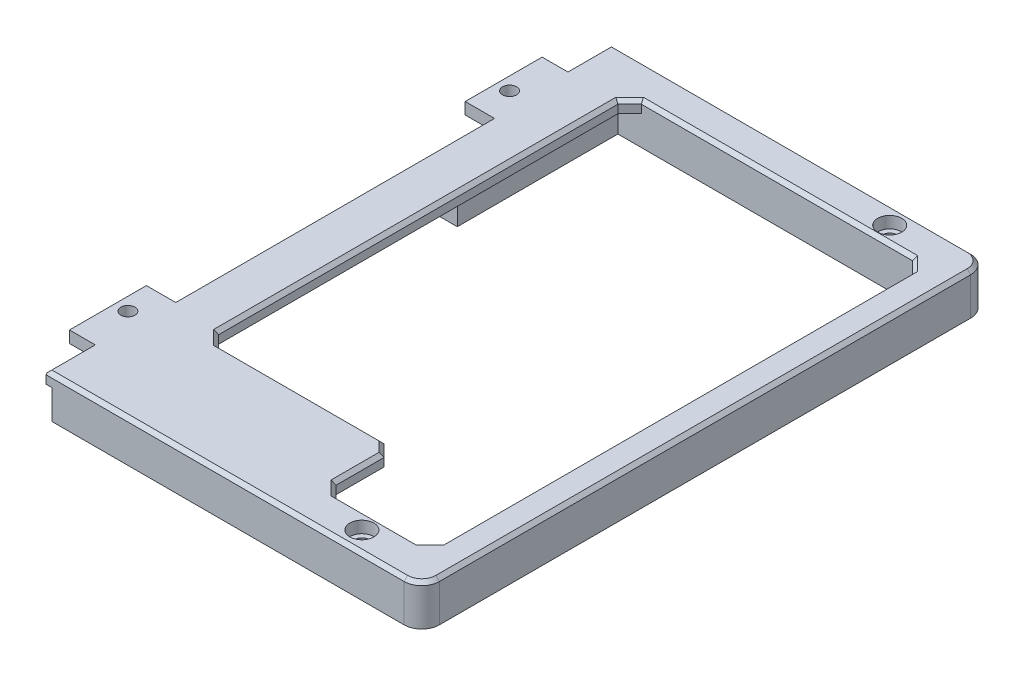
SolidWorks part; units mm, degrees
ref_plane "前视基准面" through (0, 0, 0) normal (0, 0, 1) x (1, 0, 0)
ref_plane "上视基准面" through (0, 0, 0) normal (0, 1, 0) x (1, 0, 0)
ref_plane "右视基准面" through (0, 0, 0) normal (1, 0, 0) x (0, 0, -1)
sketch "草图2" plane through (0, 0, 0) normal (1, 0, 0) x (0, 0, -1)
  line L0 (-24.1958, 3.5) -> (135.844, 3.5) construction
  line L1 (0, 0) -> (96.5, 0)
  line L2 (0, 0) -> (0, 7)
  line L3 (0, 7) -> (96.5, 7)
  line L4 (96.5, 0) -> (96.5, 7)
  dimension "D1" = 7
  dimension "D2" = 96.5
extrude "凸台-拉伸1" add sketch "草图2" along normal blind 11
sketch "草图6" plane through (0, 0, -96.5) normal (0, 0, -1) x (-1, 0, 0)
  line L0 (0, 0) -> (0, 7) construction
  line L1 (0, 5) -> (-5, 5)
  line L2 (0, 5) -> (0, 0)
  line L3 (0, 0) -> (-5, 0)
  line L4 (-5, 5) -> (-5, 0)
  line L5 (5.6103, 2.5) -> (-10.6258, 2.5) construction
  line L14 (-11, 7) -> (0, 7) construction
  line L15 (-11, 0) -> (0, 0) construction
  line M13 (0, 0) -> (0, 7)
  line M16 (-11, 0) -> (0, 0)
  dimension "D2" = 5
  dimension "D3" = 2
extrude "切除-拉伸3" cut sketch "草图6" against normal through all contours L5 L2 L1 L4 | L5 L4 M13 M16
sketch "草图7" plane through (0, 0, 0) normal (-1, 0, 0) x (0, 0, 1)
  line L0 (-88.9, 14) -> (-7.6, 14) construction
  line L1 (-75.4, 14) -> (-21.1, 14)
  line L2 (-75.4, 14) -> (-75.4, 4)
  line L3 (-75.4, 4) -> (-21.1, 4)
  line L4 (-21.1, 14) -> (-21.1, 4)
  line L5 (-7.6, 4) -> (-88.9, 4) construction
  line L12 (-48.25, 28.5535) -> (-48.25, -19.6092) construction
  line L13 (-96.5, 5) -> (-96.5, 7) construction
  line L14 (0, 7) -> (0, 5) construction
  dimension "D1" = 54.3
extrude "切除-拉伸4" cut sketch "草图7" against normal up to surface (5 mm away) up to face at (5, 2.5, -48.25)
sketch "草图8" plane through (0, 7, 0) normal (0, 1, 0) x (1, 0, 0)
  circle A1 centre (2.2, 15.75) radius 1.2
  circle A2 centre (2.2, 80.75) radius 1.2 construction
  circle A3 centre (2.2, 80.75) radius 1.2
  circle A4 centre (2.2, 15.75) radius 1.2 construction
extrude "切除-拉伸6" cut sketch "草图8" against normal through all from surface at 0 starting at face at (4, 7, -48.25)
sketch "草图10" plane through (11, 0, 0) normal (1, 0, 0) x (0, 0, -1)
  line L4 (0, 7) -> (0, 0)
  line L5 (0, 0) -> (96.5, 0)
  line L6 (96.5, 0) -> (96.5, 7)
  line L7 (96.5, 7) -> (0, 7)
  line L8 (0, 7) -> (0, 0)
  line L9 (0, 0) -> (96.5, 0)
  line L10 (96.5, 0) -> (96.5, 7)
  line L11 (96.5, 7) -> (0, 7)
  dimension "D1" = 0
extrude "凸台-拉伸2" add sketch "草图10" along normal blind 57
sketch "草图11" plane through (0, 0, 0) normal (-1, 0, 0) x (0, 0, 1)
  line L1 (-96.5, 7) -> (-88.5, 7)
  line L2 (-96.5, 7) -> (-96.5, 5)
  line L3 (-96.5, 5) -> (-88.5, 5)
  line L4 (-88.5, 7) -> (-88.5, 5)
  line L5 (0, 5) -> (-21.1, 5) construction
  line L6 (0, 7) -> (-8, 7)
  line L7 (0, 7) -> (0, 5)
  line L8 (0, 5) -> (-8, 5)
  line L9 (-8, 7) -> (-8, 5)
  dimension "D1" = 8
extrude "切除-拉伸7" cut sketch "草图11" against normal blind 4
chamfer "倒角1" distance 0.4 angle 45 2 edges at (4, 7, -92.5) (4, 7, -4)
fillet "圆角1" radius 3 2 edges at (68, 3.5, -96.5) (68, 3.5, 0)
sketch "草图12" plane through (0, 0, 0) normal (0, -1, 0) x (1, 0, 0)
  line L0 (65, -96.5) -> (5, -96.5) construction
  line L1 (10.8, -90.6) -> (65, -90.6)
  line L2 (10.8, -90.6) -> (10.8, -6.4)
  line L3 (10.8, -6.4) -> (65, -6.4)
  line L8 (12.8, -90.6) -> (63, -90.6) construction
  line L9 (10.8, -8.4) -> (10.8, -88.6) construction
  line L10 (63, -6.4) -> (12.8, -6.4) construction
  line L11 (65, -88.6) -> (65, -8.4) construction
  line L12 (65, -90.6) -> (65, -6.4)
  line L13 (65, 0) -> (5, 0) construction
  line L15 (5, 0) -> (5, -96.5) construction
  line L16 (68, -3) -> (68, -93.5) construction
  arc A0 (63, -90.6) -> (65, -88.6) centre (63, -88.6) ccw construction
  arc A8 (10.8, -88.6) -> (12.8, -90.6) centre (12.8, -88.6) ccw construction
  arc A9 (12.8, -6.4) -> (10.8, -8.4) centre (12.8, -8.4) ccw construction
  arc A10 (65, -8.4) -> (63, -6.4) centre (63, -8.4) ccw construction
  arc A11 (63, -90.6) -> (65, -88.6) centre (63, -88.6) ccw construction
  dimension "D2" = 3
  dimension "D4" = 5.9
  dimension "D5" = 6.4
  dimension "D7" = 5.8
extrude "切除-拉伸8" cut sketch "草图12" against normal offset from surface (5 mm away) 2 up to face at (2.2, 7, -16.95)
sketch "草图13" plane through (0, 5, 0) normal (0, -1, 0) x (1, 0, 0)
  line L0 (53.264, -18.639) -> (55.335, -18.6) construction
  line L1 (55.335, -18.6) -> (56.8, -20.025) construction
  line L2 (56.8, -20.025) -> (56.8, -22.08) construction
  line L3 (56.8, -22.08) -> (55.336, -23.561) construction
  line L4 (55.336, -23.561) -> (53.265, -23.6) construction
  line L5 (53.265, -23.6) -> (51.8, -22.175) construction
  line L6 (51.8, -22.175) -> (51.8, -20.12) construction
  line L7 (51.8, -20.12) -> (53.264, -18.639) construction
  line L8 (53.264, -7.339) -> (55.335, -7.3) construction
  line L9 (55.335, -7.3) -> (56.8, -8.725) construction
  line L10 (56.8, -8.725) -> (56.8, -10.78) construction
  line L11 (56.8, -10.78) -> (55.336, -12.261) construction
  line L12 (55.336, -12.261) -> (53.265, -12.3) construction
  line L13 (53.265, -12.3) -> (51.8, -10.875) construction
  line L14 (51.8, -10.875) -> (51.8, -8.82) construction
  line L15 (51.8, -8.82) -> (53.264, -7.339) construction
  line L16 (58.064, -13.039) -> (60.135, -13) construction
  line L17 (60.135, -13) -> (61.6, -14.425) construction
  line L18 (61.6, -14.425) -> (61.6, -16.48) construction
  line L19 (61.6, -16.48) -> (60.136, -17.961) construction
  line L20 (60.136, -17.961) -> (58.065, -18) construction
  line L21 (58.065, -18) -> (56.6, -16.575) construction
  line L22 (56.6, -16.575) -> (56.6, -14.52) construction
  line L23 (56.6, -14.52) -> (58.064, -13.039) construction
  line L24 (50.535, -13) -> (52, -14.425) construction
  line L25 (52, -14.425) -> (52, -16.48) construction
  line L26 (52, -16.48) -> (50.536, -17.961) construction
  line L27 (50.536, -17.961) -> (48.465, -18) construction
  line L28 (48.465, -18) -> (47, -16.575) construction
  line L29 (47, -16.575) -> (47, -14.52) construction
  line L30 (47, -14.52) -> (48.464, -13.039) construction
  line L31 (48.464, -13.039) -> (50.535, -13) construction
  line L32 (56.664, -55.179) -> (58.736, -55.14) construction
  line L33 (58.736, -55.14) -> (60.2, -56.565) construction
  line L34 (60.2, -56.565) -> (60.2, -58.62) construction
  line L35 (60.2, -58.62) -> (58.736, -60.101) construction
  line L36 (58.736, -60.101) -> (56.665, -60.14) construction
  line L37 (56.665, -60.14) -> (55.2, -58.715) construction
  line L38 (55.2, -58.715) -> (55.2, -56.66) construction
  line L39 (55.2, -56.66) -> (56.664, -55.179) construction
  line L40 (56.664, -49.179) -> (58.736, -49.14) construction
  line L41 (58.736, -49.14) -> (60.2, -50.565) construction
  line L42 (60.2, -50.565) -> (60.2, -52.62) construction
  line L43 (60.2, -52.62) -> (58.736, -54.101) construction
  line L44 (58.736, -54.101) -> (56.665, -54.14) construction
  line L45 (56.665, -54.14) -> (55.2, -52.715) construction
  line L46 (55.2, -52.715) -> (55.2, -50.66) construction
  line L47 (55.2, -50.66) -> (56.664, -49.179) construction
  line L48 (55.2, -44.66) -> (56.664, -43.179) construction
  line L49 (56.664, -43.179) -> (58.736, -43.14) construction
  line L50 (58.736, -43.14) -> (60.2, -44.565) construction
  line L51 (60.2, -44.565) -> (60.2, -46.62) construction
  line L52 (60.2, -46.62) -> (58.736, -48.101) construction
  line L53 (58.736, -48.101) -> (56.665, -48.14) construction
  line L54 (56.665, -48.14) -> (55.2, -46.715) construction
  line L55 (55.2, -46.715) -> (55.2, -44.66) construction
  line L56 (56.664, -37.179) -> (58.736, -37.14) construction
  line L57 (58.736, -37.14) -> (60.2, -38.565) construction
  line L58 (60.2, -38.565) -> (60.2, -40.62) construction
  line L59 (60.2, -40.62) -> (58.736, -42.101) construction
  line L60 (58.736, -42.101) -> (56.665, -42.14) construction
  line L61 (56.665, -42.14) -> (55.2, -40.715) construction
  line L62 (55.2, -40.715) -> (55.2, -38.66) construction
  line L63 (55.2, -38.66) -> (56.664, -37.179) construction
  line L64 (56.664, -31.179) -> (58.736, -31.14) construction
  line L65 (58.736, -31.14) -> (60.2, -32.565) construction
  line L66 (60.2, -32.565) -> (60.2, -34.62) construction
  line L67 (60.2, -34.62) -> (58.736, -36.101) construction
  line L68 (58.736, -36.101) -> (56.665, -36.14) construction
  line L69 (56.665, -36.14) -> (55.2, -34.715) construction
  line L70 (55.2, -34.715) -> (55.2, -32.66) construction
  line L71 (55.2, -32.66) -> (56.664, -31.179) construction
  line L72 (56.664, -25.179) -> (58.736, -25.14) construction
  line L73 (58.736, -25.14) -> (60.2, -26.565) construction
  line L74 (60.2, -26.565) -> (60.2, -28.62) construction
  line L75 (60.2, -28.62) -> (58.736, -30.101) construction
  line L76 (58.736, -30.101) -> (56.665, -30.14) construction
  line L77 (56.665, -30.14) -> (55.2, -28.715) construction
  line L78 (55.2, -28.715) -> (55.2, -26.66) construction
  line L79 (55.2, -26.66) -> (56.664, -25.179) construction
  line L80 (55.2, -62.657) -> (56.664, -61.176) construction
  line L81 (56.664, -61.176) -> (58.736, -61.137) construction
  line L82 (58.736, -61.137) -> (60.2, -62.562) construction
  line L83 (60.2, -62.562) -> (60.2, -64.617) construction
  line L84 (60.2, -64.617) -> (58.736, -66.098) construction
  line L85 (58.736, -66.098) -> (56.665, -66.137) construction
  line L86 (56.665, -66.137) -> (55.2, -64.712) construction
  line L87 (55.2, -64.712) -> (55.2, -62.657) construction
  line L88 (56.664, -67.179) -> (58.736, -67.14) construction
  line L89 (58.736, -67.14) -> (60.2, -68.565) construction
  line L90 (60.2, -68.565) -> (60.2, -70.62) construction
  line L91 (60.2, -70.62) -> (58.736, -72.101) construction
  line L92 (58.736, -72.101) -> (56.665, -72.14) construction
  line L93 (56.665, -72.14) -> (55.2, -70.715) construction
  line L94 (55.2, -70.715) -> (55.2, -68.66) construction
  line L95 (55.2, -68.66) -> (56.664, -67.179) construction
  line L96 (56.664, -73.182) -> (58.736, -73.143) construction
  line L97 (58.736, -73.143) -> (60.2, -74.568) construction
  line L98 (60.2, -74.568) -> (60.2, -76.623) construction
  line L99 (60.2, -76.623) -> (58.736, -78.104) construction
  line L100 (58.736, -78.104) -> (56.665, -78.143) construction
  line L101 (56.665, -78.143) -> (55.2, -76.718) construction
  line L102 (55.2, -76.718) -> (55.2, -74.663) construction
  line L103 (55.2, -74.663) -> (56.664, -73.182) construction
  line L104 (55.2, -80.662) -> (56.664, -79.181) construction
  line L105 (56.664, -79.181) -> (58.736, -79.141) construction
  line L106 (58.736, -79.141) -> (60.2, -80.566) construction
  line L107 (60.2, -80.566) -> (60.2, -82.621) construction
  line L108 (60.2, -82.621) -> (58.736, -84.102) construction
  line L109 (58.736, -84.102) -> (56.665, -84.141) construction
  line L110 (56.665, -84.141) -> (55.2, -82.716) construction
  line L111 (55.2, -82.716) -> (55.2, -80.662) construction
  line L112 (55.2, -86.62) -> (56.664, -85.139) construction
  line L113 (56.664, -85.139) -> (58.736, -85.1) construction
  line L114 (58.736, -85.1) -> (60.2, -86.525) construction
  line L115 (60.2, -86.525) -> (60.2, -88.58) construction
  line L116 (60.2, -88.58) -> (58.736, -90.061) construction
  line L117 (58.736, -90.061) -> (56.665, -90.1) construction
  line L118 (56.665, -90.1) -> (55.2, -88.675) construction
  line L119 (55.2, -88.675) -> (55.2, -86.62) construction
  line L120 (44.865, -90.1) -> (43.4, -88.675) construction
  line L121 (43.4, -88.675) -> (43.4, -86.62) construction
  line L122 (43.4, -86.62) -> (44.864, -85.139) construction
  line L123 (44.864, -85.139) -> (46.935, -85.1) construction
  line L124 (46.935, -85.1) -> (48.4, -86.525) construction
  line L125 (48.4, -86.525) -> (48.4, -88.58) construction
  line L126 (48.4, -88.58) -> (46.936, -90.061) construction
  line L127 (46.936, -90.061) -> (44.865, -90.1) construction
  line L128 (43.4, -82.716) -> (43.4, -80.662) construction
  line L129 (43.4, -80.662) -> (44.864, -79.181) construction
  line L130 (44.864, -79.181) -> (46.935, -79.141) construction
  line L131 (46.935, -79.141) -> (48.4, -80.566) construction
  line L132 (48.4, -80.566) -> (48.4, -82.621) construction
  line L133 (48.4, -82.621) -> (46.936, -84.102) construction
  line L134 (46.936, -84.102) -> (44.865, -84.141) construction
  line L135 (44.865, -84.141) -> (43.4, -82.716) construction
  line L136 (46.935, -73.143) -> (48.4, -74.568) construction
  line L137 (48.4, -74.568) -> (48.4, -76.623) construction
  line L138 (48.4, -76.623) -> (46.936, -78.104) construction
  line L139 (46.936, -78.104) -> (44.865, -78.143) construction
  line L140 (44.865, -78.143) -> (43.4, -76.718) construction
  line L141 (43.4, -76.718) -> (43.4, -74.663) construction
  line L142 (43.4, -74.663) -> (44.864, -73.182) construction
  line L143 (44.864, -73.182) -> (46.935, -73.143) construction
  line L144 (46.935, -67.14) -> (48.4, -68.565) construction
  line L145 (48.4, -68.565) -> (48.4, -70.62) construction
  line L146 (48.4, -70.62) -> (46.936, -72.101) construction
  line L147 (46.936, -72.101) -> (44.865, -72.14) construction
  line L148 (44.865, -72.14) -> (43.4, -70.715) construction
  line L149 (43.4, -70.715) -> (43.4, -68.66) construction
  line L150 (43.4, -68.66) -> (44.864, -67.179) construction
  line L151 (44.864, -67.179) -> (46.935, -67.14) construction
  line L152 (48.4, -62.562) -> (48.4, -64.617) construction
  line L153 (48.4, -64.617) -> (46.936, -66.098) construction
  line L154 (46.936, -66.098) -> (44.865, -66.137) construction
  line L155 (44.865, -66.137) -> (43.4, -64.712) construction
  line L156 (43.4, -64.712) -> (43.4, -62.657) construction
  line L157 (43.4, -62.657) -> (44.864, -61.176) construction
  line L158 (44.864, -61.176) -> (46.935, -61.137) construction
  line L159 (46.935, -61.137) -> (48.4, -62.562) construction
  line L160 (46.935, -55.14) -> (48.4, -56.565) construction
  line L161 (48.4, -56.565) -> (48.4, -58.62) construction
  line L162 (48.4, -58.62) -> (46.936, -60.101) construction
  line L163 (46.936, -60.101) -> (44.865, -60.14) construction
  line L164 (44.865, -60.14) -> (43.4, -58.715) construction
  line L165 (43.4, -58.715) -> (43.4, -56.66) construction
  line L166 (43.4, -56.66) -> (44.864, -55.179) construction
  line L167 (44.864, -55.179) -> (46.935, -55.14) construction
  line L168 (46.935, -49.14) -> (48.4, -50.565) construction
  line L169 (48.4, -50.565) -> (48.4, -52.62) construction
  line L170 (48.4, -52.62) -> (46.936, -54.101) construction
  line L171 (46.936, -54.101) -> (44.865, -54.14) construction
  line L172 (44.865, -54.14) -> (43.4, -52.715) construction
  line L173 (43.4, -52.715) -> (43.4, -50.66) construction
  line L174 (43.4, -50.66) -> (44.864, -49.179) construction
  line L175 (44.864, -49.179) -> (46.935, -49.14) construction
  line L176 (43.4, -44.66) -> (44.864, -43.179) construction
  line L177 (44.864, -43.179) -> (46.935, -43.14) construction
  line L178 (46.935, -43.14) -> (48.4, -44.565) construction
  line L179 (48.4, -44.565) -> (48.4, -46.62) construction
  line L180 (48.4, -46.62) -> (46.936, -48.101) construction
  line L181 (46.936, -48.101) -> (44.865, -48.14) construction
  line L182 (44.865, -48.14) -> (43.4, -46.715) construction
  line L183 (43.4, -46.715) -> (43.4, -44.66) construction
  line L184 (46.935, -37.14) -> (48.4, -38.565) construction
  line L185 (48.4, -38.565) -> (48.4, -40.62) construction
  line L186 (48.4, -40.62) -> (46.936, -42.101) construction
  line L187 (46.936, -42.101) -> (44.865, -42.14) construction
  line L188 (44.865, -42.14) -> (43.4, -40.715) construction
  line L189 (43.4, -40.715) -> (43.4, -38.66) construction
  line L190 (43.4, -38.66) -> (44.864, -37.179) construction
  line L191 (44.864, -37.179) -> (46.935, -37.14) construction
  line L192 (46.935, -31.14) -> (48.4, -32.565) construction
  line L193 (48.4, -32.565) -> (48.4, -34.62) construction
  line L194 (48.4, -34.62) -> (46.936, -36.101) construction
  line L195 (46.936, -36.101) -> (44.865, -36.14) construction
  line L196 (44.865, -36.14) -> (43.4, -34.715) construction
  line L197 (43.4, -34.715) -> (43.4, -32.66) construction
  line L198 (43.4, -32.66) -> (44.864, -31.179) construction
  line L199 (44.864, -31.179) -> (46.935, -31.14) construction
  line L200 (46.935, -25.14) -> (48.4, -26.565) construction
  line L201 (48.4, -26.565) -> (48.4, -28.62) construction
  line L202 (48.4, -28.62) -> (46.936, -30.101) construction
  line L203 (46.936, -30.101) -> (44.865, -30.14) construction
  line L204 (44.865, -30.14) -> (43.4, -28.715) construction
  line L205 (43.4, -28.715) -> (43.4, -26.66) construction
  line L206 (43.4, -26.66) -> (44.864, -25.179) construction
  line L207 (44.864, -25.179) -> (46.935, -25.14) construction
  line L208 (31.6, -80.662) -> (33.064, -79.181) construction
  line L209 (33.064, -79.181) -> (35.135, -79.141) construction
  line L210 (35.135, -79.141) -> (36.6, -80.566) construction
  line L211 (36.6, -80.566) -> (36.6, -82.621) construction
  line L212 (36.6, -82.621) -> (35.136, -84.102) construction
  line L213 (35.136, -84.102) -> (33.065, -84.141) construction
  line L214 (33.065, -84.141) -> (31.6, -82.716) construction
  line L215 (31.6, -82.716) -> (31.6, -80.662) construction
  line L216 (35.135, -73.143) -> (36.6, -74.568) construction
  line L217 (36.6, -74.568) -> (36.6, -76.623) construction
  line L218 (36.6, -76.623) -> (35.136, -78.104) construction
  line L219 (35.136, -78.104) -> (33.065, -78.143) construction
  line L220 (33.065, -78.143) -> (31.6, -76.718) construction
  line L221 (31.6, -76.718) -> (31.6, -74.663) construction
  line L222 (31.6, -74.663) -> (33.064, -73.182) construction
  line L223 (33.064, -73.182) -> (35.135, -73.143) construction
  line L224 (35.135, -67.14) -> (36.6, -68.565) construction
  line L225 (36.6, -68.565) -> (36.6, -70.62) construction
  line L226 (36.6, -70.62) -> (35.136, -72.101) construction
  line L227 (35.136, -72.101) -> (33.065, -72.14) construction
  line L228 (33.065, -72.14) -> (31.6, -70.715) construction
  line L229 (31.6, -70.715) -> (31.6, -68.66) construction
  line L230 (31.6, -68.66) -> (33.064, -67.179) construction
  line L231 (33.064, -67.179) -> (35.135, -67.14) construction
  line L232 (31.6, -62.657) -> (33.064, -61.176) construction
  line L233 (33.064, -61.176) -> (35.135, -61.137) construction
  line L234 (35.135, -61.137) -> (36.6, -62.562) construction
  line L235 (36.6, -62.562) -> (36.6, -64.617) construction
  line L236 (36.6, -64.617) -> (35.136, -66.098) construction
  line L237 (35.136, -66.098) -> (33.065, -66.137) construction
  line L238 (33.065, -66.137) -> (31.6, -64.712) construction
  line L239 (31.6, -64.712) -> (31.6, -62.657) construction
  line L240 (35.135, -55.14) -> (36.6, -56.565) construction
  line L241 (36.6, -56.565) -> (36.6, -58.62) construction
  line L242 (36.6, -58.62) -> (35.136, -60.101) construction
  line L243 (35.136, -60.101) -> (33.065, -60.14) construction
  line L244 (33.065, -60.14) -> (31.6, -58.715) construction
  line L245 (31.6, -58.715) -> (31.6, -56.66) construction
  line L246 (31.6, -56.66) -> (33.064, -55.179) construction
  line L247 (33.064, -55.179) -> (35.135, -55.14) construction
  line L248 (35.135, -49.14) -> (36.6, -50.565) construction
  line L249 (36.6, -50.565) -> (36.6, -52.62) construction
  line L250 (36.6, -52.62) -> (35.136, -54.101) construction
  line L251 (35.136, -54.101) -> (33.065, -54.14) construction
  line L252 (33.065, -54.14) -> (31.6, -52.715) construction
  line L253 (31.6, -52.715) -> (31.6, -50.66) construction
  line L254 (31.6, -50.66) -> (33.064, -49.179) construction
  line L255 (33.064, -49.179) -> (35.135, -49.14) construction
  line L256 (31.6, -44.66) -> (33.064, -43.179) construction
  line L257 (33.064, -43.179) -> (35.135, -43.14) construction
  line L258 (35.135, -43.14) -> (36.6, -44.565) construction
  line L259 (36.6, -44.565) -> (36.6, -46.62) construction
  line L260 (36.6, -46.62) -> (35.136, -48.101) construction
  line L261 (35.136, -48.101) -> (33.065, -48.14) construction
  line L262 (33.065, -48.14) -> (31.6, -46.715) construction
  line L263 (31.6, -46.715) -> (31.6, -44.66) construction
  line L264 (35.135, -37.14) -> (36.6, -38.565) construction
  line L265 (36.6, -38.565) -> (36.6, -40.62) construction
  line L266 (36.6, -40.62) -> (35.136, -42.101) construction
  line L267 (35.136, -42.101) -> (33.065, -42.14) construction
  line L268 (33.065, -42.14) -> (31.6, -40.715) construction
  line L269 (31.6, -40.715) -> (31.6, -38.66) construction
  line L270 (31.6, -38.66) -> (33.064, -37.179) construction
  line L271 (33.064, -37.179) -> (35.135, -37.14) construction
  line L272 (35.135, -31.14) -> (36.6, -32.565) construction
  line L273 (36.6, -32.565) -> (36.6, -34.62) construction
  line L274 (36.6, -34.62) -> (35.136, -36.101) construction
  line L275 (35.136, -36.101) -> (33.065, -36.14) construction
  line L276 (33.065, -36.14) -> (31.6, -34.715) construction
  line L277 (31.6, -34.715) -> (31.6, -32.66) construction
  line L278 (31.6, -32.66) -> (33.064, -31.179) construction
  line L279 (33.064, -31.179) -> (35.135, -31.14) construction
  line L280 (35.135, -25.14) -> (36.6, -26.565) construction
  line L281 (36.6, -26.565) -> (36.6, -28.62) construction
  line L282 (36.6, -28.62) -> (35.136, -30.101) construction
  line L283 (35.136, -30.101) -> (33.065, -30.14) construction
  line L284 (33.065, -30.14) -> (31.6, -28.715) construction
  line L285 (31.6, -28.715) -> (31.6, -26.66) construction
  line L286 (31.6, -26.66) -> (33.064, -25.179) construction
  line L287 (33.064, -25.179) -> (35.135, -25.14) construction
  line L288 (35.135, -19.14) -> (36.6, -20.565) construction
  line L289 (36.6, -20.565) -> (36.6, -22.62) construction
  line L290 (36.6, -22.62) -> (35.136, -24.101) construction
  line L291 (35.136, -24.101) -> (33.065, -24.14) construction
  line L292 (33.065, -24.14) -> (31.6, -22.715) construction
  line L293 (31.6, -22.715) -> (31.6, -20.66) construction
  line L294 (31.6, -20.66) -> (33.064, -19.179) construction
  line L295 (33.064, -19.179) -> (35.135, -19.14) construction
  line L296 (31.6, -86.62) -> (33.064, -85.139) construction
  line L297 (33.064, -85.139) -> (35.135, -85.1) construction
  line L298 (35.135, -85.1) -> (36.6, -86.525) construction
  line L299 (36.6, -86.525) -> (36.6, -88.58) construction
  line L300 (36.6, -88.58) -> (35.136, -90.061) construction
  line L301 (35.136, -90.061) -> (33.065, -90.1) construction
  line L302 (33.065, -90.1) -> (31.6, -88.675) construction
  line L303 (31.6, -88.675) -> (31.6, -86.62) construction
  line L304 (19.4, -86.62) -> (20.864, -85.139) construction
  line L305 (20.864, -85.139) -> (22.935, -85.1) construction
  line L306 (22.935, -85.1) -> (24.4, -86.525) construction
  line L307 (24.4, -86.525) -> (24.4, -88.58) construction
  line L308 (24.4, -88.58) -> (22.936, -90.061) construction
  line L309 (22.936, -90.061) -> (20.865, -90.1) construction
  line L310 (20.865, -90.1) -> (19.4, -88.675) construction
  line L311 (19.4, -88.675) -> (19.4, -86.62) construction
  line L312 (19.4, -80.662) -> (20.864, -79.181) construction
  line L313 (20.864, -79.181) -> (22.935, -79.141) construction
  line L314 (22.935, -79.141) -> (24.4, -80.566) construction
  line L315 (24.4, -80.566) -> (24.4, -82.621) construction
  line L316 (24.4, -82.621) -> (22.936, -84.102) construction
  line L317 (22.936, -84.102) -> (20.865, -84.141) construction
  line L318 (20.865, -84.141) -> (19.4, -82.716) construction
  line L319 (19.4, -82.716) -> (19.4, -80.662) construction
  line L320 (22.935, -73.143) -> (24.4, -74.568) construction
  line L321 (24.4, -74.568) -> (24.4, -76.623) construction
  line L322 (24.4, -76.623) -> (22.936, -78.104) construction
  line L323 (22.936, -78.104) -> (20.865, -78.143) construction
  line L324 (20.865, -78.143) -> (19.4, -76.718) construction
  line L325 (19.4, -76.718) -> (19.4, -74.663) construction
  line L326 (19.4, -74.663) -> (20.864, -73.182) construction
  line L327 (20.864, -73.182) -> (22.935, -73.143) construction
  line L328 (22.935, -67.14) -> (24.4, -68.565) construction
  line L329 (24.4, -68.565) -> (24.4, -70.62) construction
  line L330 (24.4, -70.62) -> (22.936, -72.101) construction
  line L331 (22.936, -72.101) -> (20.865, -72.14) construction
  line L332 (20.865, -72.14) -> (19.4, -70.715) construction
  line L333 (19.4, -70.715) -> (19.4, -68.66) construction
  line L334 (19.4, -68.66) -> (20.864, -67.179) construction
  line L335 (20.864, -67.179) -> (22.935, -67.14) construction
  line L336 (19.4, -62.657) -> (20.864, -61.176) construction
  line L337 (20.864, -61.176) -> (22.935, -61.137) construction
  line L338 (22.935, -61.137) -> (24.4, -62.562) construction
  line L339 (24.4, -62.562) -> (24.4, -64.617) construction
  line L340 (24.4, -64.617) -> (22.936, -66.098) construction
  line L341 (22.936, -66.098) -> (20.865, -66.137) construction
  line L342 (20.865, -66.137) -> (19.4, -64.712) construction
  line L343 (19.4, -64.712) -> (19.4, -62.657) construction
  line L344 (22.935, -55.14) -> (24.4, -56.565) construction
  line L345 (24.4, -56.565) -> (24.4, -58.62) construction
  line L346 (24.4, -58.62) -> (22.936, -60.101) construction
  line L347 (22.936, -60.101) -> (20.865, -60.14) construction
  line L348 (20.865, -60.14) -> (19.4, -58.715) construction
  line L349 (19.4, -58.715) -> (19.4, -56.66) construction
  line L350 (19.4, -56.66) -> (20.864, -55.179) construction
  line L351 (20.864, -55.179) -> (22.935, -55.14) construction
  line L352 (22.935, -49.14) -> (24.4, -50.565) construction
  line L353 (24.4, -50.565) -> (24.4, -52.62) construction
  line L354 (24.4, -52.62) -> (22.936, -54.101) construction
  line L355 (22.936, -54.101) -> (20.865, -54.14) construction
  line L356 (20.865, -54.14) -> (19.4, -52.715) construction
  line L357 (19.4, -52.715) -> (19.4, -50.66) construction
  line L358 (19.4, -50.66) -> (20.864, -49.179) construction
  line L359 (20.864, -49.179) -> (22.935, -49.14) construction
  line L360 (24.4, -46.62) -> (22.936, -48.101) construction
  line L361 (22.936, -48.101) -> (20.865, -48.14) construction
  line L362 (20.865, -48.14) -> (19.4, -46.715) construction
  line L363 (19.4, -46.715) -> (19.4, -44.66) construction
  line L364 (19.4, -44.66) -> (20.864, -43.179) construction
  line L365 (20.864, -43.179) -> (22.935, -43.14) construction
  line L366 (22.935, -43.14) -> (24.4, -44.565) construction
  line L367 (24.4, -44.565) -> (24.4, -46.62) construction
  line L368 (22.935, -37.14) -> (24.4, -38.565) construction
  line L369 (24.4, -38.565) -> (24.4, -40.62) construction
  line L370 (24.4, -40.62) -> (22.936, -42.101) construction
  line L371 (22.936, -42.101) -> (20.865, -42.14) construction
  line L372 (20.865, -42.14) -> (19.4, -40.715) construction
  line L373 (19.4, -40.715) -> (19.4, -38.66) construction
  line L374 (19.4, -38.66) -> (20.864, -37.179) construction
  line L375 (20.864, -37.179) -> (22.935, -37.14) construction
  line L376 (22.935, -31.14) -> (24.4, -32.565) construction
  line L377 (24.4, -32.565) -> (24.4, -34.62) construction
  line L378 (24.4, -34.62) -> (22.936, -36.101) construction
  line L379 (22.936, -36.101) -> (20.865, -36.14) construction
  line L380 (20.865, -36.14) -> (19.4, -34.715) construction
  line L381 (19.4, -34.715) -> (19.4, -32.66) construction
  line L382 (19.4, -32.66) -> (20.864, -31.179) construction
  line L383 (20.864, -31.179) -> (22.935, -31.14) construction
  line L384 (20.864, -25.179) -> (22.935, -25.14) construction
  line L385 (22.935, -25.14) -> (24.4, -26.565) construction
  line L386 (24.4, -26.565) -> (24.4, -28.62) construction
  line L387 (24.4, -28.62) -> (22.936, -30.101) construction
  line L388 (22.936, -30.101) -> (20.865, -30.14) construction
  line L389 (20.865, -30.14) -> (19.4, -28.715) construction
  line L390 (19.4, -28.715) -> (19.4, -26.66) construction
  line L391 (19.4, -26.66) -> (20.864, -25.179) construction
  line L392 (22.935, -19.14) -> (24.4, -20.565) construction
  line L393 (24.4, -20.565) -> (24.4, -22.62) construction
  line L394 (24.4, -22.62) -> (22.936, -24.101) construction
  line L395 (22.936, -24.101) -> (20.865, -24.14) construction
  line L396 (20.865, -24.14) -> (19.4, -22.715) construction
  line L397 (19.4, -22.715) -> (19.4, -20.66) construction
  line L398 (19.4, -20.66) -> (20.864, -19.179) construction
  line L399 (20.864, -19.179) -> (22.935, -19.14) construction
  line L400 (53.264, -18.639) -> (55.335, -18.6)
  line L401 (55.335, -18.6) -> (56.8, -20.025)
  line L402 (56.8, -20.025) -> (56.8, -22.08)
  line L403 (56.8, -22.08) -> (55.336, -23.561)
  line L404 (55.336, -23.561) -> (53.265, -23.6)
  line L405 (53.265, -23.6) -> (51.8, -22.175)
  line L406 (51.8, -22.175) -> (51.8, -20.12)
  line L407 (51.8, -20.12) -> (53.264, -18.639)
  line L408 (53.264, -7.339) -> (55.335, -7.3)
  line L409 (55.335, -7.3) -> (56.8, -8.725)
  line L410 (56.8, -8.725) -> (56.8, -10.78)
  line L411 (56.8, -10.78) -> (55.336, -12.261)
  line L412 (55.336, -12.261) -> (53.265, -12.3)
  line L413 (53.265, -12.3) -> (51.8, -10.875)
  line L414 (51.8, -10.875) -> (51.8, -8.82)
  line L415 (51.8, -8.82) -> (53.264, -7.339)
  line L416 (58.064, -13.039) -> (60.135, -13)
  line L417 (60.135, -13) -> (61.6, -14.425)
  line L418 (61.6, -14.425) -> (61.6, -16.48)
  line L419 (61.6, -16.48) -> (60.136, -17.961)
  line L420 (60.136, -17.961) -> (58.065, -18)
  line L421 (58.065, -18) -> (56.6, -16.575)
  line L422 (56.6, -16.575) -> (56.6, -14.52)
  line L423 (56.6, -14.52) -> (58.064, -13.039)
  line L424 (50.535, -13) -> (52, -14.425)
  line L425 (52, -14.425) -> (52, -16.48)
  line L426 (52, -16.48) -> (50.536, -17.961)
  line L427 (50.536, -17.961) -> (48.465, -18)
  line L428 (48.465, -18) -> (47, -16.575)
  line L429 (47, -16.575) -> (47, -14.52)
  line L430 (47, -14.52) -> (48.464, -13.039)
  line L431 (48.464, -13.039) -> (50.535, -13)
  line L432 (56.664, -55.179) -> (58.736, -55.14)
  line L433 (58.736, -55.14) -> (60.2, -56.565)
  line L434 (60.2, -56.565) -> (60.2, -58.62)
  line L435 (60.2, -58.62) -> (58.736, -60.101)
  line L436 (58.736, -60.101) -> (56.665, -60.14)
  line L437 (56.665, -60.14) -> (55.2, -58.715)
  line L438 (55.2, -58.715) -> (55.2, -56.66)
  line L439 (55.2, -56.66) -> (56.664, -55.179)
  line L440 (56.664, -49.179) -> (58.736, -49.14)
  line L441 (58.736, -49.14) -> (60.2, -50.565)
  line L442 (60.2, -50.565) -> (60.2, -52.62)
  line L443 (60.2, -52.62) -> (58.736, -54.101)
  line L444 (58.736, -54.101) -> (56.665, -54.14)
  line L445 (56.665, -54.14) -> (55.2, -52.715)
  line L446 (55.2, -52.715) -> (55.2, -50.66)
  line L447 (55.2, -50.66) -> (56.664, -49.179)
  line L448 (55.2, -44.66) -> (56.664, -43.179)
  line L449 (56.664, -43.179) -> (58.736, -43.14)
  line L450 (58.736, -43.14) -> (60.2, -44.565)
  line L451 (60.2, -44.565) -> (60.2, -46.62)
  line L452 (60.2, -46.62) -> (58.736, -48.101)
  line L453 (58.736, -48.101) -> (56.665, -48.14)
  line L454 (56.665, -48.14) -> (55.2, -46.715)
  line L455 (55.2, -46.715) -> (55.2, -44.66)
  line L456 (56.664, -37.179) -> (58.736, -37.14)
  line L457 (58.736, -37.14) -> (60.2, -38.565)
  line L458 (60.2, -38.565) -> (60.2, -40.62)
  line L459 (60.2, -40.62) -> (58.736, -42.101)
  line L460 (58.736, -42.101) -> (56.665, -42.14)
  line L461 (56.665, -42.14) -> (55.2, -40.715)
  line L462 (55.2, -40.715) -> (55.2, -38.66)
  line L463 (55.2, -38.66) -> (56.664, -37.179)
  line L464 (56.664, -31.179) -> (58.736, -31.14)
  line L465 (58.736, -31.14) -> (60.2, -32.565)
  line L466 (60.2, -32.565) -> (60.2, -34.62)
  line L467 (60.2, -34.62) -> (58.736, -36.101)
  line L468 (58.736, -36.101) -> (56.665, -36.14)
  line L469 (56.665, -36.14) -> (55.2, -34.715)
  line L470 (55.2, -34.715) -> (55.2, -32.66)
  line L471 (55.2, -32.66) -> (56.664, -31.179)
  line L472 (56.664, -25.179) -> (58.736, -25.14)
  line L473 (58.736, -25.14) -> (60.2, -26.565)
  line L474 (60.2, -26.565) -> (60.2, -28.62)
  line L475 (60.2, -28.62) -> (58.736, -30.101)
  line L476 (58.736, -30.101) -> (56.665, -30.14)
  line L477 (56.665, -30.14) -> (55.2, -28.715)
  line L478 (55.2, -28.715) -> (55.2, -26.66)
  line L479 (55.2, -26.66) -> (56.664, -25.179)
  line L480 (55.2, -62.657) -> (56.664, -61.176)
  line L481 (56.664, -61.176) -> (58.736, -61.137)
  line L482 (58.736, -61.137) -> (60.2, -62.562)
  line L483 (60.2, -62.562) -> (60.2, -64.617)
  line L484 (60.2, -64.617) -> (58.736, -66.098)
  line L485 (58.736, -66.098) -> (56.665, -66.137)
  line L486 (56.665, -66.137) -> (55.2, -64.712)
  line L487 (55.2, -64.712) -> (55.2, -62.657)
  line L488 (56.664, -67.179) -> (58.736, -67.14)
  line L489 (58.736, -67.14) -> (60.2, -68.565)
  line L490 (60.2, -68.565) -> (60.2, -70.62)
  line L491 (60.2, -70.62) -> (58.736, -72.101)
  line L492 (58.736, -72.101) -> (56.665, -72.14)
  line L493 (56.665, -72.14) -> (55.2, -70.715)
  line L494 (55.2, -70.715) -> (55.2, -68.66)
  line L495 (55.2, -68.66) -> (56.664, -67.179)
  line L496 (56.664, -73.182) -> (58.736, -73.143)
  line L497 (58.736, -73.143) -> (60.2, -74.568)
  line L498 (60.2, -74.568) -> (60.2, -76.623)
  line L499 (60.2, -76.623) -> (58.736, -78.104)
  line L500 (58.736, -78.104) -> (56.665, -78.143)
  line L501 (56.665, -78.143) -> (55.2, -76.718)
  line L502 (55.2, -76.718) -> (55.2, -74.663)
  line L503 (55.2, -74.663) -> (56.664, -73.182)
  line L504 (55.2, -80.662) -> (56.664, -79.181)
  line L505 (56.664, -79.181) -> (58.736, -79.141)
  line L506 (58.736, -79.141) -> (60.2, -80.566)
  line L507 (60.2, -80.566) -> (60.2, -82.621)
  line L508 (60.2, -82.621) -> (58.736, -84.102)
  line L509 (58.736, -84.102) -> (56.665, -84.141)
  line L510 (56.665, -84.141) -> (55.2, -82.716)
  line L511 (55.2, -82.716) -> (55.2, -80.662)
  line L512 (55.2, -86.62) -> (56.664, -85.139)
  line L513 (56.664, -85.139) -> (58.736, -85.1)
  line L514 (58.736, -85.1) -> (60.2, -86.525)
  line L515 (60.2, -86.525) -> (60.2, -88.58)
  line L516 (60.2, -88.58) -> (58.736, -90.061)
  line L517 (58.736, -90.061) -> (56.665, -90.1)
  line L518 (56.665, -90.1) -> (55.2, -88.675)
  line L519 (55.2, -88.675) -> (55.2, -86.62)
  line L520 (44.865, -90.1) -> (43.4, -88.675)
  line L521 (43.4, -88.675) -> (43.4, -86.62)
  line L522 (43.4, -86.62) -> (44.864, -85.139)
  line L523 (44.864, -85.139) -> (46.935, -85.1)
  line L524 (46.935, -85.1) -> (48.4, -86.525)
  line L525 (48.4, -86.525) -> (48.4, -88.58)
  line L526 (48.4, -88.58) -> (46.936, -90.061)
  line L527 (46.936, -90.061) -> (44.865, -90.1)
  line L528 (43.4, -82.716) -> (43.4, -80.662)
  line L529 (43.4, -80.662) -> (44.864, -79.181)
  line L530 (44.864, -79.181) -> (46.935, -79.141)
  line L531 (46.935, -79.141) -> (48.4, -80.566)
  line L532 (48.4, -80.566) -> (48.4, -82.621)
  line L533 (48.4, -82.621) -> (46.936, -84.102)
  line L534 (46.936, -84.102) -> (44.865, -84.141)
  line L535 (44.865, -84.141) -> (43.4, -82.716)
  line L536 (46.935, -73.143) -> (48.4, -74.568)
  line L537 (48.4, -74.568) -> (48.4, -76.623)
  line L538 (48.4, -76.623) -> (46.936, -78.104)
  line L539 (46.936, -78.104) -> (44.865, -78.143)
  line L540 (44.865, -78.143) -> (43.4, -76.718)
  line L541 (43.4, -76.718) -> (43.4, -74.663)
  line L542 (43.4, -74.663) -> (44.864, -73.182)
  line L543 (44.864, -73.182) -> (46.935, -73.143)
  line L544 (46.935, -67.14) -> (48.4, -68.565)
  line L545 (48.4, -68.565) -> (48.4, -70.62)
  line L546 (48.4, -70.62) -> (46.936, -72.101)
  line L547 (46.936, -72.101) -> (44.865, -72.14)
  line L548 (44.865, -72.14) -> (43.4, -70.715)
  line L549 (43.4, -70.715) -> (43.4, -68.66)
  line L550 (43.4, -68.66) -> (44.864, -67.179)
  line L551 (44.864, -67.179) -> (46.935, -67.14)
  line L552 (48.4, -62.562) -> (48.4, -64.617)
  line L553 (48.4, -64.617) -> (46.936, -66.098)
  line L554 (46.936, -66.098) -> (44.865, -66.137)
  line L555 (44.865, -66.137) -> (43.4, -64.712)
  line L556 (43.4, -64.712) -> (43.4, -62.657)
  line L557 (43.4, -62.657) -> (44.864, -61.176)
  line L558 (44.864, -61.176) -> (46.935, -61.137)
  line L559 (46.935, -61.137) -> (48.4, -62.562)
  line L560 (46.935, -55.14) -> (48.4, -56.565)
  line L561 (48.4, -56.565) -> (48.4, -58.62)
  line L562 (48.4, -58.62) -> (46.936, -60.101)
  line L563 (46.936, -60.101) -> (44.865, -60.14)
  line L564 (44.865, -60.14) -> (43.4, -58.715)
  line L565 (43.4, -58.715) -> (43.4, -56.66)
  line L566 (43.4, -56.66) -> (44.864, -55.179)
  line L567 (44.864, -55.179) -> (46.935, -55.14)
  line L568 (46.935, -49.14) -> (48.4, -50.565)
  line L569 (48.4, -50.565) -> (48.4, -52.62)
  line L570 (48.4, -52.62) -> (46.936, -54.101)
  line L571 (46.936, -54.101) -> (44.865, -54.14)
  line L572 (44.865, -54.14) -> (43.4, -52.715)
  line L573 (43.4, -52.715) -> (43.4, -50.66)
  line L574 (43.4, -50.66) -> (44.864, -49.179)
  line L575 (44.864, -49.179) -> (46.935, -49.14)
  line L576 (43.4, -44.66) -> (44.864, -43.179)
  line L577 (44.864, -43.179) -> (46.935, -43.14)
  line L578 (46.935, -43.14) -> (48.4, -44.565)
  line L579 (48.4, -44.565) -> (48.4, -46.62)
  line L580 (48.4, -46.62) -> (46.936, -48.101)
  line L581 (46.936, -48.101) -> (44.865, -48.14)
  line L582 (44.865, -48.14) -> (43.4, -46.715)
  line L583 (43.4, -46.715) -> (43.4, -44.66)
  line L584 (46.935, -37.14) -> (48.4, -38.565)
  line L585 (48.4, -38.565) -> (48.4, -40.62)
  line L586 (48.4, -40.62) -> (46.936, -42.101)
  line L587 (46.936, -42.101) -> (44.865, -42.14)
  line L588 (44.865, -42.14) -> (43.4, -40.715)
  line L589 (43.4, -40.715) -> (43.4, -38.66)
  line L590 (43.4, -38.66) -> (44.864, -37.179)
  line L591 (44.864, -37.179) -> (46.935, -37.14)
  line L592 (46.935, -31.14) -> (48.4, -32.565)
  line L593 (48.4, -32.565) -> (48.4, -34.62)
  line L594 (48.4, -34.62) -> (46.936, -36.101)
  line L595 (46.936, -36.101) -> (44.865, -36.14)
  line L596 (44.865, -36.14) -> (43.4, -34.715)
  line L597 (43.4, -34.715) -> (43.4, -32.66)
  line L598 (43.4, -32.66) -> (44.864, -31.179)
  line L599 (44.864, -31.179) -> (46.935, -31.14)
  line L600 (46.935, -25.14) -> (48.4, -26.565)
  line L601 (48.4, -26.565) -> (48.4, -28.62)
  line L602 (48.4, -28.62) -> (46.936, -30.101)
  line L603 (46.936, -30.101) -> (44.865, -30.14)
  line L604 (44.865, -30.14) -> (43.4, -28.715)
  line L605 (43.4, -28.715) -> (43.4, -26.66)
  line L606 (43.4, -26.66) -> (44.864, -25.179)
  line L607 (44.864, -25.179) -> (46.935, -25.14)
  line L608 (31.6, -80.662) -> (33.064, -79.181)
  line L609 (33.064, -79.181) -> (35.135, -79.141)
  line L610 (35.135, -79.141) -> (36.6, -80.566)
  line L611 (36.6, -80.566) -> (36.6, -82.621)
  line L612 (36.6, -82.621) -> (35.136, -84.102)
  line L613 (35.136, -84.102) -> (33.065, -84.141)
  line L614 (33.065, -84.141) -> (31.6, -82.716)
  line L615 (31.6, -82.716) -> (31.6, -80.662)
  line L616 (35.135, -73.143) -> (36.6, -74.568)
  line L617 (36.6, -74.568) -> (36.6, -76.623)
  line L618 (36.6, -76.623) -> (35.136, -78.104)
  line L619 (35.136, -78.104) -> (33.065, -78.143)
  line L620 (33.065, -78.143) -> (31.6, -76.718)
  line L621 (31.6, -76.718) -> (31.6, -74.663)
  line L622 (31.6, -74.663) -> (33.064, -73.182)
  line L623 (33.064, -73.182) -> (35.135, -73.143)
  line L624 (35.135, -67.14) -> (36.6, -68.565)
  line L625 (36.6, -68.565) -> (36.6, -70.62)
  line L626 (36.6, -70.62) -> (35.136, -72.101)
  line L627 (35.136, -72.101) -> (33.065, -72.14)
  line L628 (33.065, -72.14) -> (31.6, -70.715)
  line L629 (31.6, -70.715) -> (31.6, -68.66)
  line L630 (31.6, -68.66) -> (33.064, -67.179)
  line L631 (33.064, -67.179) -> (35.135, -67.14)
  line L632 (31.6, -62.657) -> (33.064, -61.176)
  line L633 (33.064, -61.176) -> (35.135, -61.137)
  line L634 (35.135, -61.137) -> (36.6, -62.562)
  line L635 (36.6, -62.562) -> (36.6, -64.617)
  line L636 (36.6, -64.617) -> (35.136, -66.098)
  line L637 (35.136, -66.098) -> (33.065, -66.137)
  line L638 (33.065, -66.137) -> (31.6, -64.712)
  line L639 (31.6, -64.712) -> (31.6, -62.657)
  line L640 (35.135, -55.14) -> (36.6, -56.565)
  line L641 (36.6, -56.565) -> (36.6, -58.62)
  line L642 (36.6, -58.62) -> (35.136, -60.101)
  line L643 (35.136, -60.101) -> (33.065, -60.14)
  line L644 (33.065, -60.14) -> (31.6, -58.715)
  line L645 (31.6, -58.715) -> (31.6, -56.66)
  line L646 (31.6, -56.66) -> (33.064, -55.179)
  line L647 (33.064, -55.179) -> (35.135, -55.14)
  line L648 (35.135, -49.14) -> (36.6, -50.565)
  line L649 (36.6, -50.565) -> (36.6, -52.62)
  line L650 (36.6, -52.62) -> (35.136, -54.101)
  line L651 (35.136, -54.101) -> (33.065, -54.14)
  line L652 (33.065, -54.14) -> (31.6, -52.715)
  line L653 (31.6, -52.715) -> (31.6, -50.66)
  line L654 (31.6, -50.66) -> (33.064, -49.179)
  line L655 (33.064, -49.179) -> (35.135, -49.14)
  line L656 (31.6, -44.66) -> (33.064, -43.179)
  line L657 (33.064, -43.179) -> (35.135, -43.14)
  line L658 (35.135, -43.14) -> (36.6, -44.565)
  line L659 (36.6, -44.565) -> (36.6, -46.62)
  line L660 (36.6, -46.62) -> (35.136, -48.101)
  line L661 (35.136, -48.101) -> (33.065, -48.14)
  line L662 (33.065, -48.14) -> (31.6, -46.715)
  line L663 (31.6, -46.715) -> (31.6, -44.66)
  line L664 (35.135, -37.14) -> (36.6, -38.565)
  line L665 (36.6, -38.565) -> (36.6, -40.62)
  line L666 (36.6, -40.62) -> (35.136, -42.101)
  line L667 (35.136, -42.101) -> (33.065, -42.14)
  line L668 (33.065, -42.14) -> (31.6, -40.715)
  line L669 (31.6, -40.715) -> (31.6, -38.66)
  line L670 (31.6, -38.66) -> (33.064, -37.179)
  line L671 (33.064, -37.179) -> (35.135, -37.14)
  line L672 (35.135, -31.14) -> (36.6, -32.565)
  line L673 (36.6, -32.565) -> (36.6, -34.62)
  line L674 (36.6, -34.62) -> (35.136, -36.101)
  line L675 (35.136, -36.101) -> (33.065, -36.14)
  line L676 (33.065, -36.14) -> (31.6, -34.715)
  line L677 (31.6, -34.715) -> (31.6, -32.66)
  line L678 (31.6, -32.66) -> (33.064, -31.179)
  line L679 (33.064, -31.179) -> (35.135, -31.14)
  line L680 (35.135, -25.14) -> (36.6, -26.565)
  line L681 (36.6, -26.565) -> (36.6, -28.62)
  line L682 (36.6, -28.62) -> (35.136, -30.101)
  line L683 (35.136, -30.101) -> (33.065, -30.14)
  line L684 (33.065, -30.14) -> (31.6, -28.715)
  line L685 (31.6, -28.715) -> (31.6, -26.66)
  line L686 (31.6, -26.66) -> (33.064, -25.179)
  line L687 (33.064, -25.179) -> (35.135, -25.14)
  line L688 (35.135, -19.14) -> (36.6, -20.565)
  line L689 (36.6, -20.565) -> (36.6, -22.62)
  line L690 (36.6, -22.62) -> (35.136, -24.101)
  line L691 (35.136, -24.101) -> (33.065, -24.14)
  line L692 (33.065, -24.14) -> (31.6, -22.715)
  line L693 (31.6, -22.715) -> (31.6, -20.66)
  line L694 (31.6, -20.66) -> (33.064, -19.179)
  line L695 (33.064, -19.179) -> (35.135, -19.14)
  line L696 (31.6, -86.62) -> (33.064, -85.139)
  line L697 (33.064, -85.139) -> (35.135, -85.1)
  line L698 (35.135, -85.1) -> (36.6, -86.525)
  line L699 (36.6, -86.525) -> (36.6, -88.58)
  line L700 (36.6, -88.58) -> (35.136, -90.061)
  line L701 (35.136, -90.061) -> (33.065, -90.1)
  line L702 (33.065, -90.1) -> (31.6, -88.675)
  line L703 (31.6, -88.675) -> (31.6, -86.62)
  line L704 (19.4, -86.62) -> (20.864, -85.139)
  line L705 (20.864, -85.139) -> (22.935, -85.1)
  line L706 (22.935, -85.1) -> (24.4, -86.525)
  line L707 (24.4, -86.525) -> (24.4, -88.58)
  line L708 (24.4, -88.58) -> (22.936, -90.061)
  line L709 (22.936, -90.061) -> (20.865, -90.1)
  line L710 (20.865, -90.1) -> (19.4, -88.675)
  line L711 (19.4, -88.675) -> (19.4, -86.62)
  line L712 (19.4, -80.662) -> (20.864, -79.181)
  line L713 (20.864, -79.181) -> (22.935, -79.141)
  line L714 (22.935, -79.141) -> (24.4, -80.566)
  line L715 (24.4, -80.566) -> (24.4, -82.621)
  line L716 (24.4, -82.621) -> (22.936, -84.102)
  line L717 (22.936, -84.102) -> (20.865, -84.141)
  line L718 (20.865, -84.141) -> (19.4, -82.716)
  line L719 (19.4, -82.716) -> (19.4, -80.662)
  line L720 (22.935, -73.143) -> (24.4, -74.568)
  line L721 (24.4, -74.568) -> (24.4, -76.623)
  line L722 (24.4, -76.623) -> (22.936, -78.104)
  line L723 (22.936, -78.104) -> (20.865, -78.143)
  line L724 (20.865, -78.143) -> (19.4, -76.718)
  line L725 (19.4, -76.718) -> (19.4, -74.663)
  line L726 (19.4, -74.663) -> (20.864, -73.182)
  line L727 (20.864, -73.182) -> (22.935, -73.143)
  line L728 (22.935, -67.14) -> (24.4, -68.565)
  line L729 (24.4, -68.565) -> (24.4, -70.62)
  line L730 (24.4, -70.62) -> (22.936, -72.101)
  line L731 (22.936, -72.101) -> (20.865, -72.14)
  line L732 (20.865, -72.14) -> (19.4, -70.715)
  line L733 (19.4, -70.715) -> (19.4, -68.66)
  line L734 (19.4, -68.66) -> (20.864, -67.179)
  line L735 (20.864, -67.179) -> (22.935, -67.14)
  line L736 (19.4, -62.657) -> (20.864, -61.176)
  line L737 (20.864, -61.176) -> (22.935, -61.137)
  line L738 (22.935, -61.137) -> (24.4, -62.562)
  line L739 (24.4, -62.562) -> (24.4, -64.617)
  line L740 (24.4, -64.617) -> (22.936, -66.098)
  line L741 (22.936, -66.098) -> (20.865, -66.137)
  line L742 (20.865, -66.137) -> (19.4, -64.712)
  line L743 (19.4, -64.712) -> (19.4, -62.657)
  line L744 (22.935, -55.14) -> (24.4, -56.565)
  line L745 (24.4, -56.565) -> (24.4, -58.62)
  line L746 (24.4, -58.62) -> (22.936, -60.101)
  line L747 (22.936, -60.101) -> (20.865, -60.14)
  line L748 (20.865, -60.14) -> (19.4, -58.715)
  line L749 (19.4, -58.715) -> (19.4, -56.66)
  line L750 (19.4, -56.66) -> (20.864, -55.179)
  line L751 (20.864, -55.179) -> (22.935, -55.14)
  line L752 (22.935, -49.14) -> (24.4, -50.565)
  line L753 (24.4, -50.565) -> (24.4, -52.62)
  line L754 (24.4, -52.62) -> (22.936, -54.101)
  line L755 (22.936, -54.101) -> (20.865, -54.14)
  line L756 (20.865, -54.14) -> (19.4, -52.715)
  line L757 (19.4, -52.715) -> (19.4, -50.66)
  line L758 (19.4, -50.66) -> (20.864, -49.179)
  line L759 (20.864, -49.179) -> (22.935, -49.14)
  line L760 (24.4, -46.62) -> (22.936, -48.101)
  line L761 (22.936, -48.101) -> (20.865, -48.14)
  line L762 (20.865, -48.14) -> (19.4, -46.715)
  line L763 (19.4, -46.715) -> (19.4, -44.66)
  line L764 (19.4, -44.66) -> (20.864, -43.179)
  line L765 (20.864, -43.179) -> (22.935, -43.14)
  line L766 (22.935, -43.14) -> (24.4, -44.565)
  line L767 (24.4, -44.565) -> (24.4, -46.62)
  line L768 (22.935, -37.14) -> (24.4, -38.565)
  line L769 (24.4, -38.565) -> (24.4, -40.62)
  line L770 (24.4, -40.62) -> (22.936, -42.101)
  line L771 (22.936, -42.101) -> (20.865, -42.14)
  line L772 (20.865, -42.14) -> (19.4, -40.715)
  line L773 (19.4, -40.715) -> (19.4, -38.66)
  line L774 (19.4, -38.66) -> (20.864, -37.179)
  line L775 (20.864, -37.179) -> (22.935, -37.14)
  line L776 (22.935, -31.14) -> (24.4, -32.565)
  line L777 (24.4, -32.565) -> (24.4, -34.62)
  line L778 (24.4, -34.62) -> (22.936, -36.101)
  line L779 (22.936, -36.101) -> (20.865, -36.14)
  line L780 (20.865, -36.14) -> (19.4, -34.715)
  line L781 (19.4, -34.715) -> (19.4, -32.66)
  line L782 (19.4, -32.66) -> (20.864, -31.179)
  line L783 (20.864, -31.179) -> (22.935, -31.14)
  line L784 (20.864, -25.179) -> (22.935, -25.14)
  line L785 (22.935, -25.14) -> (24.4, -26.565)
  line L786 (24.4, -26.565) -> (24.4, -28.62)
  line L787 (24.4, -28.62) -> (22.936, -30.101)
  line L788 (22.936, -30.101) -> (20.865, -30.14)
  line L789 (20.865, -30.14) -> (19.4, -28.715)
  line L790 (19.4, -28.715) -> (19.4, -26.66)
  line L791 (19.4, -26.66) -> (20.864, -25.179)
  line L792 (22.935, -19.14) -> (24.4, -20.565)
  line L793 (24.4, -20.565) -> (24.4, -22.62)
  line L794 (24.4, -22.62) -> (22.936, -24.101)
  line L795 (22.936, -24.101) -> (20.865, -24.14)
  line L796 (20.865, -24.14) -> (19.4, -22.715)
  line L797 (19.4, -22.715) -> (19.4, -20.66)
  line L798 (19.4, -20.66) -> (20.864, -19.179)
  line L799 (20.864, -19.179) -> (22.935, -19.14)
sketch "草图16" plane through (0, 5, 0) normal (0, -1, 0) x (1, 0, 0)
  line L0 (45, -6.4) -> (63, -6.4)
  line L1 (10.8, -6.4) -> (65, -6.4) construction
  line L2 (63, -6.4) -> (63, -90.6)
  line L3 (63, -90.6) -> (12.8, -90.6)
  line L4 (12.8, -90.6) -> (12.8, -18.6)
  line L5 (65, -90.6) -> (10.8, -90.6) construction
  line L6 (12.8, -18.6) -> (45, -18.6)
  line L7 (45, -18.6) -> (45, -6.4)
  line L8 (10.8, -90.6) -> (10.8, -6.4) construction
  line L9 (65, -6.4) -> (65, -90.6) construction
  dimension "D1" = 12.2
  dimension "D2" = 18
  dimension "D3" = 2
  dimension "D4" = 2
extrude "切除-拉伸9" cut sketch "草图16" against normal through all
chamfer "倒角2" distance 2 angle 45 6 edges at (63, 6, -6.4) (63, 6, -90.6) (12.8, 6, -90.6) (12.8, 6, -18.6) (45, 6, -18.6) (45, 6, -6.4)
chamfer "倒角3" distance 0.6 angle 45 17 edges at (34.7, 7, -96.5) (67.1213, 7, -95.6213) (68, 7, -48.25) (67.1213, 7, -0.8787) (34.7, 7, 0) (62, 7, -89.6) (63, 7, -48.5) (62, 7, -7.4) (54, 7, -6.4) (46, 7, -7.4) (45, 7, -12.5) (44, 7, -17.6) (37.9, 7, -90.6) (13.8, 7, -89.6) (12.8, 7, -54.6) (13.8, 7, -19.6) (28.9, 7, -18.6)
sketch "草图17" plane through (0, 5, 0) normal (0, -1, 0) x (1, 0, 0)
  line L3 (68, -3) -> (68, -93.5) construction
  line L6 (10.8, -6.4) -> (47, -6.4) construction
  line L7 (19.6, -14.4) -> (32.6, -14.4)
  line L8 (19.6, -14.4) -> (19.6, -6.4)
  line L9 (19.6, -6.4) -> (32.6, -6.4)
  line L10 (32.6, -14.4) -> (32.6, -6.4)
  dimension "D1" = 13
  dimension "D2" = 35.4
  dimension "D3" = 8
extrude "切除-拉伸10" cut sketch "草图17" against normal blind 0.6
sketch "草图18" plane through (0, 0, 0) normal (0, -1, 0) x (1, 0, 0)
  line L0 (65, -6.4) -> (10.8, -6.4) construction
  line L1 (10.8, -6.4) -> (10.8, -90.6) construction
  line L2 (34.7083, -6.4) -> (10.8, -6.4)
  line L3 (10.8, -6.4) -> (10.8, -63.25)
  line L4 (5, 0) -> (5, -96.5) construction
  line L5 (5, -33.25) -> (5, -63.25)
  line L6 (5, -63.25) -> (10.8, -63.25)
  line L7 (7.8, -33.25) -> (7.8, -1.2)
  line L8 (5, -33.25) -> (7.8, -33.25)
  line L9 (7.8, -1.2) -> (34.7083, -1.2)
  line L10 (34.7083, -1.2) -> (34.7083, -6.4)
  line L11 (65, 0) -> (5, 0) construction
  line L12 (-12.9445, -48.25) -> (16.1464, -48.25) construction
  line L13 (65, -96.5) -> (5, -96.5) construction
  dimension "D1" = 30
  dimension "D2" = 1.2
  dimension "D3" = 3
extrude "切除-拉伸11" cut sketch "草图18" against normal blind 4
chamfer "倒角4" distance 1.5 angle 45 3 edges at (7.8, 2, -33.25) (34.7083, 2, -1.2) (7.8, 2, -1.2)
sketch "草图19" plane through (0, 7, 0) normal (0, 1, 0) x (1, 0, 0)
  line L1 (54.4, 3.4) -> (54.4, 93.3) construction
  line L2 (68, 93.5) -> (68, 3) construction
  line L3 (65, 0) -> (4, 0) construction
  line L5 (4, 96.5) -> (65, 96.5) construction
  circle A0 centre (15.9, 11.5) radius 2.5 construction
  circle A1 centre (15.9, 11.5) radius 2.5 construction
  circle A2 centre (15.9, 11.5) radius 2.05 construction
  circle A3 centre (54.4, 3.4) radius 2.05
  circle A4 centre (54.4, 93.3) radius 2.05
  point P15 (54.4, 94)
  dimension "D2" = 13.6
  dimension "D3" = 4.1
  dimension "D4" = 3.4
  dimension "D6" = 3.2
extrude "切除-拉伸12" cut sketch "草图19" against normal blind 2
sketch "草图20" plane through (0, 5, 0) normal (0, 1, 0) x (1, 0, 0)
  circle A0 centre (54.4, 3.4) radius 1.2
  circle A1 centre (54.4, 93.3) radius 1.2
  dimension "D1" = 2.4
extrude "切除-拉伸13" cut sketch "草图20" against normal through all
